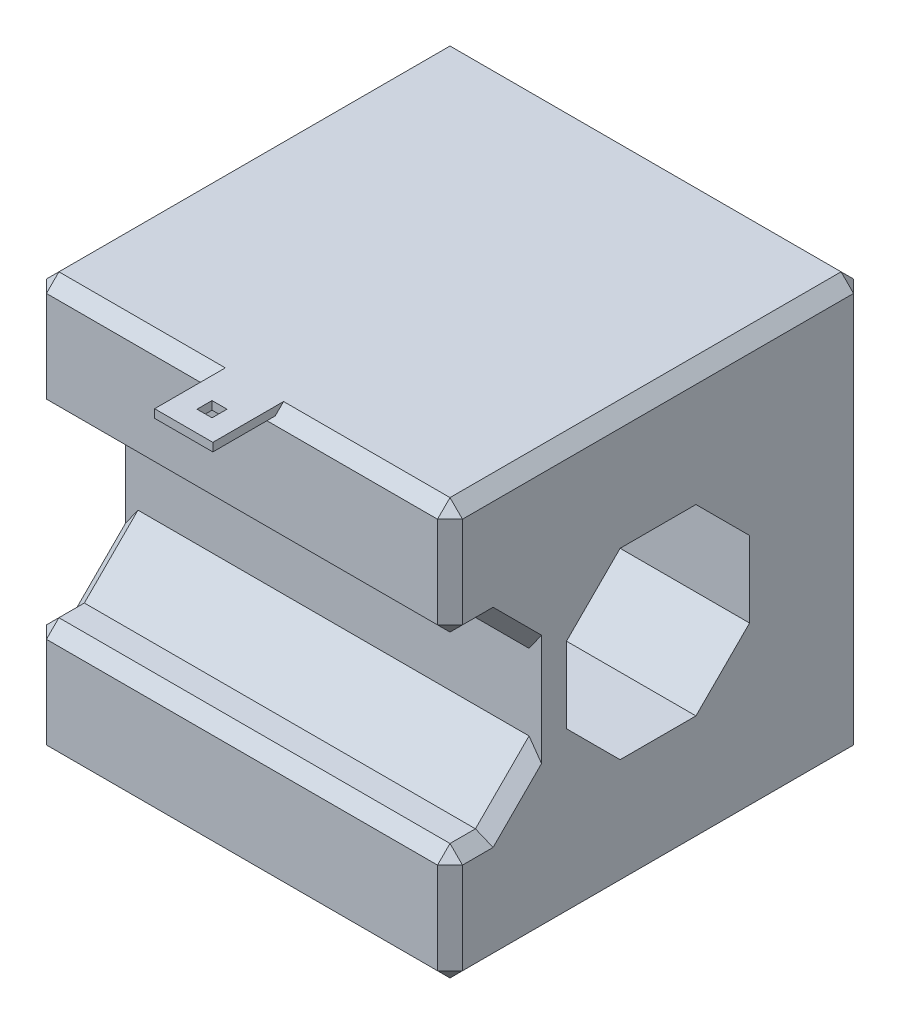
SolidWorks part; units mm, degrees
ref_plane "Front" through (0, 0, 0) normal (0, 0, 1) x (1, 0, 0)
ref_plane "Top" through (0, 0, 0) normal (0, 1, 0) x (1, 0, 0)
ref_plane "Right" through (0, 0, 0) normal (1, 0, 0) x (0, 0, -1)
sketch "Sketch1" plane through (0, 0, 0) normal (0, 0, 1) x (1, 0, 0)
  line L1 (0, 0) -> (50, 0)
  line L2 (0, 0) -> (0, 50)
  line L3 (0, 50) -> (50, 50)
  line L4 (50, 0) -> (50, 50)
  dimension "D1" = 50
extrude "Boss-Extrude1" add sketch "Sketch1" along normal blind 50
sketch "Sketch2" plane through (0, 0, 0) normal (-1, 0, 0) x (0, 0, 1)
  line L0 (50, 50) -> (50, 0) construction
  line L1 (14, 36) -> (36, 36) construction
  line L2 (14, 36) -> (14, 14) construction
  line L3 (14, 14) -> (36, 14) construction
  line L4 (36, 36) -> (36, 14) construction
  line L5 (14, 36) -> (36, 14) construction
  line L6 (14, 14) -> (36, 36) construction
  line L7 (61, 36) -> (39, 36) construction
  line L8 (61, 36) -> (61, 14) construction
  line L9 (61, 14) -> (39, 14) construction
  line L10 (39, 36) -> (39, 14) construction
  line L11 (61, 36) -> (39, 14) construction
  line L12 (61, 14) -> (39, 36) construction
  line L13 (25, 50) -> (25, 25) construction
  line L14 (50, 50) -> (0, 50) construction
  line L15 (25, 25) -> (0, 25) construction
  line L16 (0, 50) -> (0, 0) construction
  line L18 (36, 29.5563) -> (29.5563, 36)
  line L19 (29.5563, 36) -> (20.4437, 36)
  line L20 (20.4437, 36) -> (14, 29.5563)
  line L21 (14, 29.5563) -> (14, 20.4437)
  line L22 (14, 20.4437) -> (20.4437, 14)
  line L23 (20.4437, 14) -> (29.5563, 14)
  line L24 (29.5563, 14) -> (36, 20.4437)
  line L25 (36, 20.4437) -> (36, 29.5563)
  line L26 (54.5563, 36) -> (45.4437, 36)
  line L27 (45.4437, 36) -> (39, 29.5563)
  line L28 (39, 29.5563) -> (39, 20.4437)
  line L29 (39, 20.4437) -> (45.4437, 14)
  line L30 (45.4437, 14) -> (54.5563, 14)
  line L31 (54.5563, 14) -> (61, 20.4437)
  line L32 (61, 20.4437) -> (61, 29.5563)
  line L33 (61, 29.5563) -> (54.5563, 36)
  circle A0 centre (25, 25) radius 11 construction
  circle A1 centre (50, 25) radius 11 construction
  point P0 (25, 25)
  point P5 (50, 25)
  dimension "D1" = 22
extrude "Cut-Extrude1" cut sketch "Sketch2" against normal through all
chamfer "Chamfer1" distance 1.5 angle 45 24 edges at (0, 25, 0) (25, 50, 0) (0, 50, 25) (0, 14, 47.7218) (0, 17.2218, 42.2218) (0, 32.7782, 42.2218) (0, 36, 47.7218) (50, 25, 0) (25, 0, 0) (0, 43, 50) (0, 7, 50) (0, 0, 25) (50, 50, 25) (25, 50, 50) (50, 43, 50) (25, 36, 50) (50, 36, 47.7218) (50, 32.7782, 42.2218) (50, 17.2218, 42.2218) (50, 14, 47.7218) (25, 14, 50) (50, 0, 25) (50, 7, 50) (25, 0, 50)
sketch "Sketch3" plane through (0, 0, 50) normal (0, 0, 1) x (1, 0, 0)
  line L0 (1.5, 50) -> (48.5, 50) construction
  line L1 (21.5, 50) -> (28.5, 50)
  line L2 (21.5, 50) -> (21.5, 49)
  line L3 (21.5, 49) -> (28.5, 49)
  line L4 (28.5, 50) -> (28.5, 49)
  point P6 (25, 50)
  dimension "D1" = 1
  dimension "D2" = 7
extrude "Boss-Extrude2" add sketch "Sketch3" along normal blind 7 and the other way blind 10
sketch "Sketch4" plane through (0, 49, 0) normal (0, -1, 0) x (1, 0, 0)
  line L0 (25, 57) -> (25, 54.5) construction
  line L1 (24.1, 54.5) -> (25.9, 54.5)
  line L2 (24.1, 54.5) -> (24.1, 52.7)
  line L3 (24.1, 52.7) -> (25.9, 52.7)
  line L4 (25.9, 54.5) -> (25.9, 52.7)
  line L5 (21.5, 57) -> (28.5, 57) construction
  dimension "D1" = 2.5
  dimension "D2" = 1.8
extrude "Cut-Extrude2" cut sketch "Sketch4" against normal blind 7
